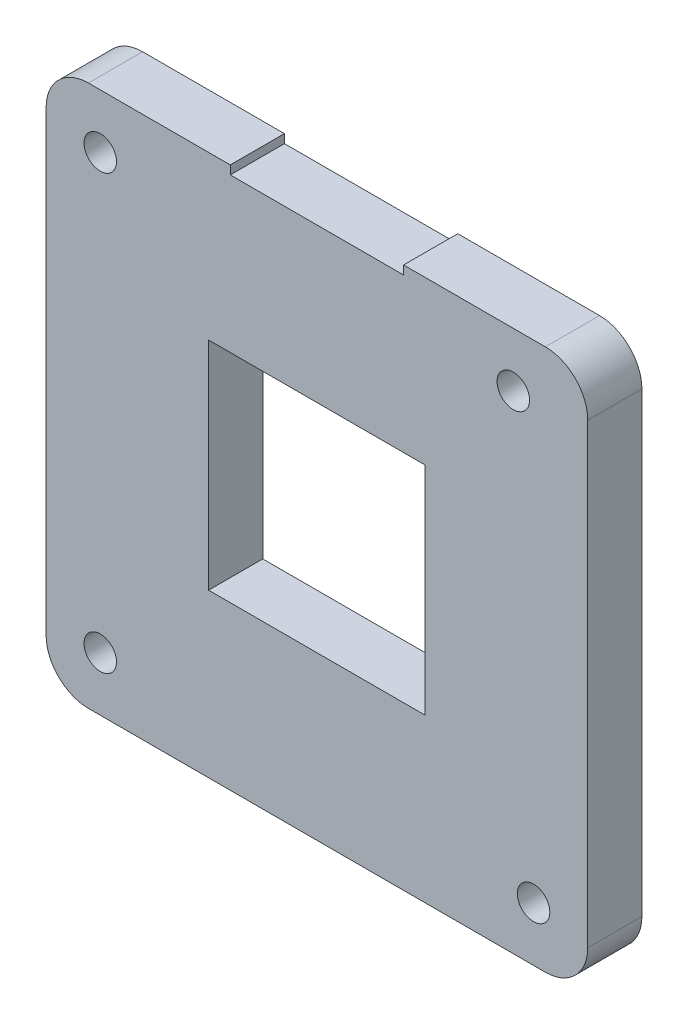
SolidWorks part; units mm, degrees
ref_plane "Front Plane" through (0, 0, 0) normal (0, 0, 1) x (1, 0, 0)
ref_plane "Top Plane" through (0, 0, 0) normal (0, 1, 0) x (1, 0, 0)
ref_plane "Right Plane" through (0, 0, 0) normal (1, 0, 0) x (0, 0, -1)
sketch "Sketch1" plane through (0, 0, 0) normal (0, 0, 1) x (1, 0, 0)
  line L0 (-21.09, 25) -> (21.09, 25)
  line L1 (-25, 21.09) -> (-25, -21.09)
  line L2 (-21.09, -25) -> (20.7574, -25)
  line L3 (25, 21.09) -> (25, -21.09)
  line L4 (21.09, -25) -> (20.7574, -25)
  arc A0 (-21.09, 25) -> (-25, 21.09) centre (-21.09, 21.09) ccw
  arc A1 (-25, -21.09) -> (-21.09, -25) centre (-21.09, -21.09) ccw
  arc A2 (21.09, 25) -> (25, 21.09) centre (21.09, 21.09) cw
  arc A3 (25, -21.09) -> (21.09, -25) centre (21.09, -21.09) cw
  point P2 (0, 25)
  point P17 (-25, 0)
  dimension "D1" = 3.91
  dimension "D2" = 42.18
  dimension "D3" = 42.18
extrude "Boss-Extrude1" add sketch "Sketch1" along normal blind 5 contours L0 A2 L3 A3 L4 L2 A1 L1 A0
sketch "Sketch2" plane through (0, 0, 5) normal (0, 0, 1) x (1, 0, 0)
  line L8 (-10, -10) -> (10, -10)
  line L9 (10, -10) -> (10, 10)
  line L10 (10, 10) -> (-10, 10)
  line L11 (-10, 10) -> (-10, -10)
  line L12 (-10, -10) -> (10, -10)
  line L13 (10, -10) -> (10, 10)
  line L14 (10, 10) -> (-10, 10)
  line L15 (-10, 10) -> (-10, -10)
  dimension "D1" = 15
extrude "Cut-Extrude1" cut sketch "Sketch2" against normal blind 5
sketch "Sketch5" plane through (0, 0, 5) normal (0, 0, 1) x (1, 0, 0)
  line L0 (-21.09, 25) -> (21.09, 25) construction
  line L1 (-25, 21.09) -> (-25, -21.09) construction
  line L3 (-21.09, -25) -> (21.09, -25) construction
  line L4 (25, 21.09) -> (25, -21.09) construction
  circle A0 centre (-20, 20) radius 1.5
  circle A1 centre (18.1305, 20) radius 1.5
  circle A2 centre (-20, -20) radius 1.5
  circle A3 centre (20, -20) radius 1.5
  dimension "D3" = 3
  dimension "D4" = 3
  dimension "D5" = 3
  dimension "D6" = 3
  dimension "D1" = 5
  dimension "D2" = 5
  dimension "D7" = 5
  dimension "D8" = 5
  dimension "D9" = 5
  dimension "D10" = 5
extrude "Cut-Extrude2" cut sketch "Sketch5" against normal through all
sketch "Sketch6" plane through (0, 0, 0) normal (0, 0, -1) x (-1, 0, 0)
  line L0 (21.09, 25) -> (-21.09, 25) construction
  line L1 (-8, 25) -> (8, 25)
  line L2 (-8, 25) -> (-8, 24.2)
  line L3 (-8, 24.2) -> (8, 24.2)
  line L4 (8, 25) -> (8, 24.2)
  point P6 (0, 24.2)
  dimension "D1" = 0.8
  dimension "D2" = 16
extrude "Cut-Extrude3" cut sketch "Sketch6" against normal through all
